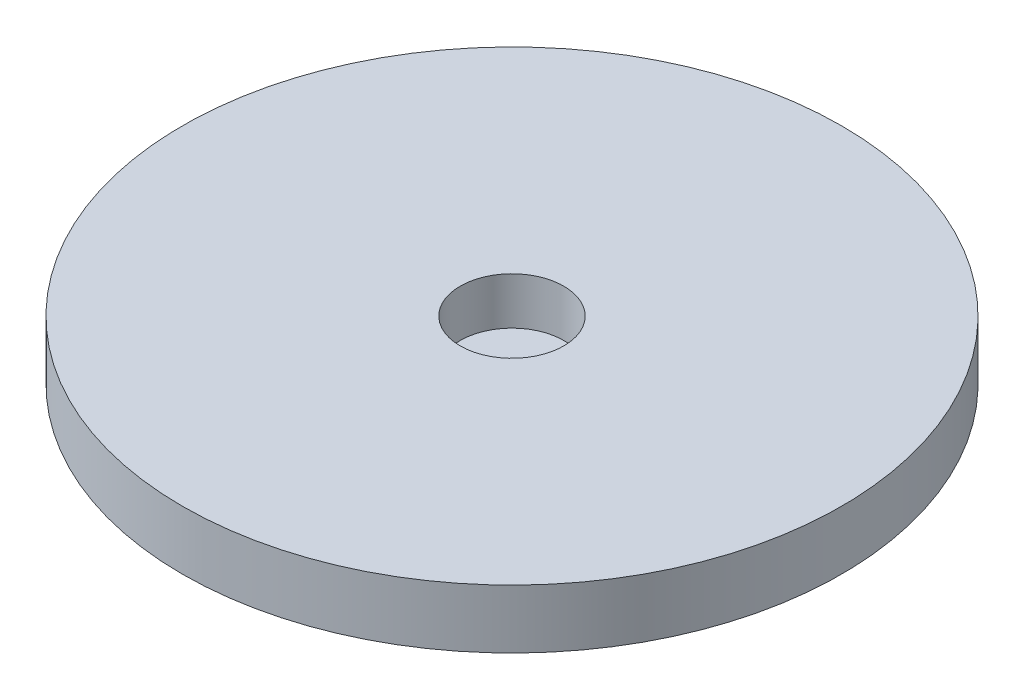
SolidWorks part; units mm, degrees
ref_plane "Front Plane" through (0, 0, 0) normal (0, 0, 1) x (1, 0, 0)
ref_plane "Top Plane" through (0, 0, 0) normal (0, 1, 0) x (1, 0, 0)
ref_plane "Right Plane" through (0, 0, 0) normal (1, 0, 0) x (0, 0, -1)
sketch "Sketch1" plane through (0, 0, 0) normal (0, 1, 0) x (1, 0, 0)
  circle A0 centre (0, 0) radius 70
extrude "Boss-Extrude2" add sketch "Sketch1" along normal blind 12.5
sketch "Sketch3" plane through (0, 12.5, 0) normal (0, 1, 0) x (1, 0, 0)
  circle A0 centre (0, 0) radius 11
extrude "Cut-Extrude1" cut sketch "Sketch3" against normal blind 10
